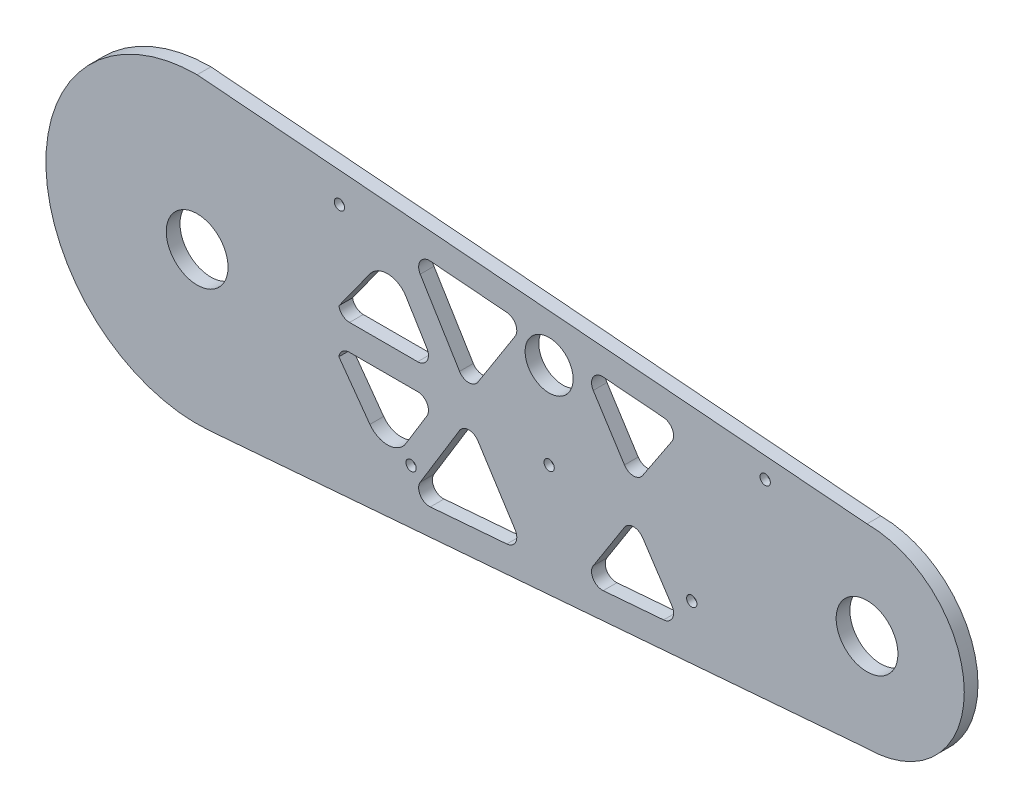
SolidWorks part; units mm, degrees
other "Marca1"
sketch "Croquis3" plane through (-70, -70, 6.35) normal (0, 0, 1) x (1, 0, 0)
material "6061-O (SS)"
ref_plane "Front Plane" through (0, 0, 0) normal (0, 0, 1) x (1, 0, 0)
ref_plane "Top Plane" through (0, 0, 0) normal (0, 1, 0) x (1, 0, 0)
ref_plane "Right Plane" through (0, 0, 0) normal (1, 0, 0) x (0, 0, -1)
sketch "Sketch1" plane through (0, 0, 0) normal (0, 0, 1) x (1, 0, 0)
  line L0 (0, 70) -> (310, 45)
  line L1 (5.1714, -69.8087) -> (310, -45)
  line L2 (0, 0) -> (310, 0) construction
  line L3 (107.899, 49.2595) -> (143.3142, 46.4034)
  line L4 (70.5232, 6) -> (102.03, 6)
  line L5 (219.6238, 32.8105) -> (206.1309, 12.4175)
  line L6 (197.7459, 12.4871) -> (183.2969, 35.1335)
  line L7 (162.8785, 6) -> (162.8785, -6) construction
  line L8 (258.6323, 64.5867) -> (258.6323, 39.5867) construction
  line L9 (147.1275, 38.7303) -> (129.9162, 11.7546)
  line L10 (121.433, 11.8395) -> (103.229, 41.6712)
  line L11 (98.117, 50.0484) -> (42.0027, 50.0484) construction
  line L12 (187.9139, 42.8067) -> (215.8558, 40.5533)
  line L13 (162.8785, 44.8257) -> (162.8785, 6) construction
  line L14 (67.1248, 64.5867) -> (162.8785, 35) construction
  line L15 (201.8849, 6) -> (201.8849, 41.68) construction
  line L16 (125.6066, 5) -> (125.6066, 47.8315) construction
  line L17 (96.5904, 29.5131) -> (106.2981, 13.6045)
  line L18 (125.6066, -5) -> (125.6066, -47.8315) construction
  line L19 (201.8849, -6) -> (201.8849, -41.68) construction
  line L20 (162.8785, -44.8257) -> (162.8785, -6) construction
  line L21 (98.117, -50.0484) -> (42.0027, -50.0484) construction
  line L22 (96.5904, -29.5131) -> (106.2981, -13.6045)
  line L23 (67.1248, 64.5867) -> (409.6974, 64.5867) construction
  line L24 (187.9139, -42.8067) -> (215.8558, -40.5533)
  line L25 (121.433, -11.8395) -> (103.229, -41.6712)
  line L26 (147.1275, -38.7303) -> (129.9162, -11.7546)
  line L27 (162.8785, 0) -> (258.6323, 64.5867) construction
  line L28 (67.1248, 64.5867) -> (67.1248, 39.5867) construction
  line L29 (197.7459, -12.4871) -> (183.2969, -35.1335)
  line L30 (219.6238, -32.8105) -> (206.1309, -12.4175)
  line L31 (70.5232, -6) -> (102.03, -6)
  line L32 (107.899, -49.2595) -> (143.3142, -46.4034)
  line L33 (0, -6.35) -> (0, 6.35) construction
  line L34 (67.1248, 39.5867) -> (162.8785, 35) construction
  line L35 (162.8785, 35) -> (67.6719, 24.0904) construction
  line L36 (79.9417, 30.1512) -> (65.583, 10.2294)
  line L37 (79.9417, -30.1512) -> (65.583, -10.2294)
  arc A0 (65.583, 10.2294) -> (70.5232, 6) centre (70.5232, 11) ccw
  arc A1 (310, -45) -> (310, 45) centre (310, 0) ccw
  circle A2 centre (0, 0) radius 14.2938
  circle A3 centre (310, 0) radius 14.2939
  arc A4 (79.9417, 30.1512) -> (96.5904, 29.5131) centre (88.0542, 24.3041) cw
  arc A5 (79.9417, -30.1512) -> (96.5904, -29.5131) centre (88.0542, -24.3041) ccw
  arc A6 (0, 70) -> (5.1714, -69.8087) centre (0, 0) ccw
  arc A7 (187.9139, 42.8067) -> (183.2969, 35.1335) centre (187.512, 37.8229) ccw
  arc A8 (219.6238, 32.8105) -> (215.8558, 40.5533) centre (215.4539, 35.5695) ccw
  arc A9 (206.1309, 12.4175) -> (197.7459, 12.4871) centre (201.961, 15.1765) cw
  circle A10 centre (162.8785, 35) radius 11.1125
  arc A13 (102.03, 6) -> (106.2981, 13.6045) centre (102.03, 11) ccw
  arc A14 (121.433, 11.8395) -> (129.9162, 11.7546) centre (125.7011, 14.444) ccw
  arc A15 (147.1275, 38.7303) -> (143.3142, 46.4034) centre (142.9123, 41.4196) ccw
  arc A16 (107.899, 49.2595) -> (103.229, 41.6712) centre (107.4971, 44.2757) ccw
  arc A17 (107.899, -49.2595) -> (103.229, -41.6712) centre (107.4971, -44.2757) cw
  arc A18 (147.1275, -38.7303) -> (143.3142, -46.4034) centre (142.9123, -41.4196) cw
  arc A19 (121.433, -11.8395) -> (129.9162, -11.7546) centre (125.7011, -14.444) cw
  arc A20 (102.03, -6) -> (106.2981, -13.6045) centre (102.03, -11) cw
  arc A24 (206.1309, -12.4175) -> (197.7459, -12.4871) centre (201.961, -15.1765) ccw
  arc A25 (219.6238, -32.8105) -> (215.8558, -40.5533) centre (215.4539, -35.5695) cw
  arc A26 (187.9139, -42.8067) -> (183.2969, -35.1335) centre (187.512, -37.8229) cw
  arc A29 (65.583, -10.2294) -> (70.5232, -6) centre (70.5232, -11) cw
  point P31 (177.8851, 43.6155)
  point P42 (187.6504, 6)
  point P44 (88.7465, 42.3671)
  point P45 (138.1067, 6)
  point P79 (88.7465, -42.3671)
  point P100 (138.1067, -6)
  point P101 (187.6504, -6)
  point P102 (177.8851, -43.6155)
  point P104 (0, 0)
  point P114 (310, 0)
  point P119 (0.2114, 0.3175)
  dimension "D2" = 45
  dimension "D3" = 12.7
  dimension "D4" = 28.5877
  dimension "D6" = 12
  dimension "D11" = 5
  dimension "D12" = 70
  dimension "D13" = 25
  dimension "D8" = 5
  dimension "D14" = 12
  dimension "D15" = 25
  dimension "D16" = 310
  dimension "D17" = 22.225
  dimension "D5" = 28.5877
  dimension "D19" = 10
  dimension "D20" = 10
  dimension "D7" = 6
  dimension "D9" = 9.279
  dimension "D10" = 34
  dimension "D18" = 35
extrude "Boss-Extrude1" add sketch "Sketch1" along normal blind 6.35
sketch "Sketch2" plane through (0, 0, 6.35) normal (0, 0, 1) x (1, 0, 0)
  line L0 (263.0927, 39.4927) -> (-0.4655, 64.9983)
  line L1 (4.6885, -64.8307) -> (263.1366, -39.5384)
  arc A0 (-0.4655, 64.9983) -> (4.6885, -64.8307) centre (0, 0) ccw
  arc A1 (263.1366, -39.5384) -> (270.3186, -23.7999) centre (262.1626, -29.5859) ccw
  circle A2 centre (0, 0) radius 40
  arc A3 (270.292, 23.7623) -> (270.3186, -23.7999) centre (303.867, 0) ccw
  arc A4 (270.292, 23.7623) -> (263.0927, 39.4927) centre (262.1295, 29.5392) ccw
  dimension "D1" = 10
  dimension "D2" = 41.133
  dimension "D3" = 65
ref_plane "Plane1" through (0, 0, 10) normal (0, 0, 1) x (1, 0, 0)
sketch "Croquis1" plane through (0, 0, 6.35) normal (0, 0, 1) x (1, 0, 0)
  circle A1 centre (98.9956, -37.0901) radius 2.3813
  circle A2 centre (228.8774, -26.5196) radius 2.3813
  point P20 (0, 0)
  dimension "D5" = 4.7625
  dimension "D1" = 4.7625
extrude "Cortar-Extruir1" cut sketch "Croquis1" against normal blind 50
sketch "Croquis4" plane through (0, 0, 0) normal (0, 0, -1) x (-1, 0, 0)
  circle A0 centre (-228.8774, -26.5196) radius 5
  circle A1 centre (-98.9956, -37.0901) radius 5
  dimension "D1" = 10
extrude "Cortar-Extruir2" cut sketch "Croquis4" against normal blind 3.175
sketch "Croquis5" plane through (0, 0, 0) normal (0, 0, -1) x (-1, 0, 0)
  line L0 (-162.8785, 35) -> (-162.8785, -35.6506) construction
  line L1 (-193.2674, -35.6506) -> (-132.4897, -35.6506) construction
  circle A0 centre (-162.8785, -5) radius 5
  point P6 (-162.8785, -35.6506)
  dimension "D2" = 10
  dimension "D1" = 40
extrude "Cortar-Extruir3" cut sketch "Croquis5" against normal blind 3.175
sketch "Croquis6" plane through (0, 0, 0) normal (0, 0, -1) x (-1, 0, 0)
  circle A0 centre (-162.8785, -5) radius 2.3813
  dimension "D1" = 4.7625
extrude "Cortar-Extruir4" cut sketch "Croquis6" against normal blind 10
sketch "Croquis7" plane through (0, 0, 0) normal (0, 0, -1) x (-1, 0, 0)
  line L0 (-228.8774, -26.5196) -> (-98.9956, -37.0901) construction
  line L1 (-98.9956, -37.0901) -> (-65.8414, 50.869) construction
  line L2 (-228.8774, -26.5196) -> (-262.8716, 39.2101) construction
  circle A0 centre (-65.8414, 50.869) radius 2.3813
  circle A1 centre (-262.8716, 39.2101) radius 2.3813
  dimension "D5" = 4.7625
  dimension "D1" = 94
  dimension "D2" = 106
  dimension "D3" = 74
  dimension "D4" = 238
extrude "Cortar-Extruir5" cut sketch "Croquis7" against normal blind 10
sketch "Croquis8" plane through (0, 0, 0) normal (0, 0, -1) x (-1, 0, 0)
  circle A0 centre (-262.8716, 39.2101) radius 5
  circle A1 centre (-65.8414, 50.869) radius 5
  dimension "D1" = 10
  dimension "D2" = 10
extrude "Cortar-Extruir6" cut sketch "Croquis8" against normal blind 3.16
